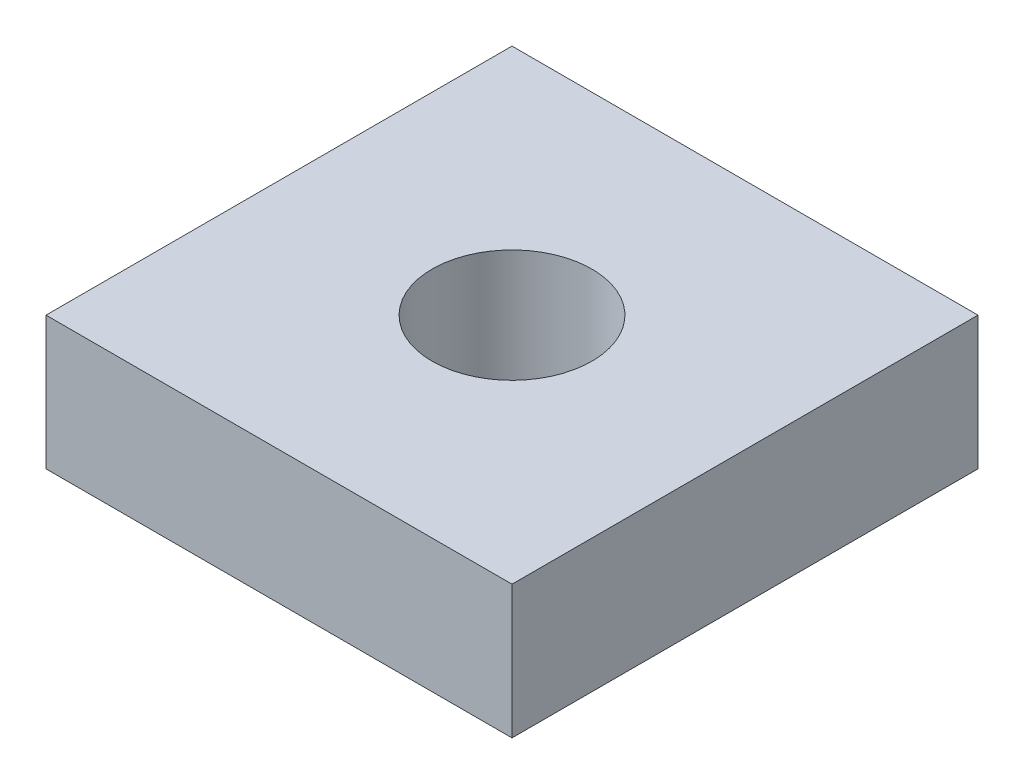
SolidWorks part; units mm, degrees
ref_plane "Front Plane" through (0, 0, 0) normal (0, 0, 1) x (1, 0, 0)
ref_plane "Top Plane" through (0, 0, 0) normal (0, 1, 0) x (1, 0, 0)
ref_plane "Right Plane" through (0, 0, 0) normal (1, 0, 0) x (0, 0, -1)
sketch "Sketch1" plane through (0, 0, 0) normal (0, 1, 0) x (1, 0, 0)
  line L1 (-17.5, -17.5) -> (17.5, -17.5)
  line L2 (-17.5, -17.5) -> (-17.5, 17.5)
  line L3 (-17.5, 17.5) -> (17.5, 17.5)
  line L4 (17.5, -17.5) -> (17.5, 17.5)
  line L5 (-17.5, -17.5) -> (17.5, 17.5) construction
  line L6 (-17.5, 17.5) -> (17.5, -17.5) construction
  circle A0 centre (0, 0) radius 6
  point P0 (0, 0)
  dimension "D3" = 12
  dimension "D1" = 35
  dimension "D2" = 35
extrude "Boss-Extrude1" add sketch "Sketch1" along normal blind 10
